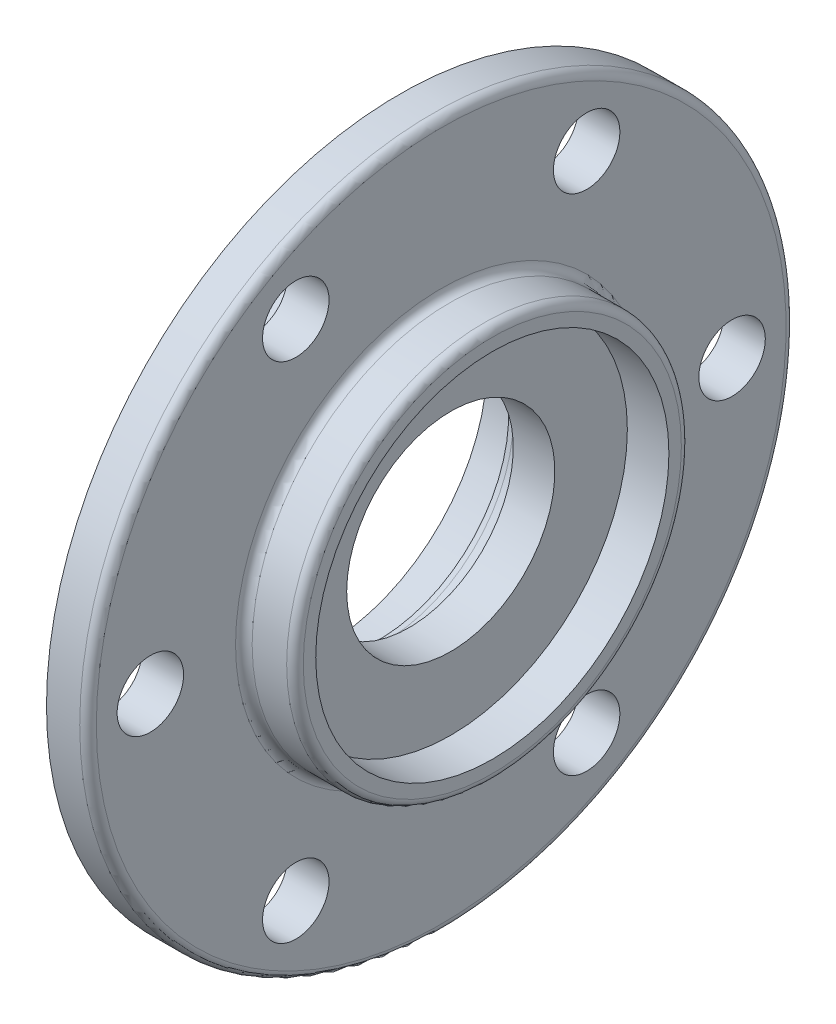
SolidWorks part; units mm, degrees
ref_plane "Front Plane" through (0, 0, 0) normal (0, 0, 1) x (1, 0, 0)
ref_plane "Top Plane" through (0, 0, 0) normal (0, 1, 0) x (1, 0, 0)
ref_plane "Right Plane" through (0, 0, 0) normal (1, 0, 0) x (0, 0, -1)
sketch "Sketch1" plane through (0, 0, 0) normal (0, 0, 1) x (1, 0, 0)
  line L0 (0, 0) -> (85.1756, 0) construction
  line L1 (0, 45) -> (18, 45)
  line L2 (18, 45) -> (18, 85)
  line L3 (18, 85) -> (26, 85)
  line L4 (28, 83) -> (28, 49.5)
  line L5 (30, 47.5) -> (38.3, 47.5)
  line L6 (40.3, 45.5) -> (40.3, 42.5)
  line L7 (40.3, 42.5) -> (30.3, 42.5)
  line L8 (30.3, 42.5) -> (30.3, 25.05)
  line L9 (30.3, 25.05) -> (20.3, 25.05)
  line L10 (20.3, 25.05) -> (20.3, 31)
  line L12 (13, 31.238) -> (13, 37)
  line L13 (11, 39) -> (0, 39)
  line L14 (0, 39) -> (0, 45)
  line L15 (20.3, 31) -> (14.35, 31)
  line L16 (14.35, 31) -> (13, 31.238)
  arc A0 (38.3, 47.5) -> (40.3, 45.5) centre (38.3, 45.5) cw
  arc A1 (13, 37) -> (11, 39) centre (11, 37) ccw
  arc A2 (28, 49.5) -> (30, 47.5) centre (30, 49.5) ccw
  arc A3 (26, 85) -> (28, 83) centre (26, 83) cw
  point P18 (35.3, 42.5)
  point P24 (13, 39)
  dimension "D16" = 2
  dimension "D1" = 50.1
  dimension "D2" = 7.3
  dimension "D3" = 5.95
  dimension "D4" = 10
  dimension "D5" = 62
  dimension "D6" = 90
  dimension "D7" = 78
  dimension "D8" = 170
  dimension "D9" = 13
  dimension "D10" = 10
  dimension "D11" = 85
  dimension "D12" = 10
  dimension "D13" = 5
  dimension "D14" = 10
  dimension "D15" = 18
revolve "Revolve1" add sketch "Sketch1" angle 360 about L0
sketch "Sketch2" plane through (28, 0, 0) normal (1, 0, 0) x (0, 0, -1)
  circle A0 centre (0, 0) radius 70 construction
  circle A1 centre (70, 0) radius 8
  circle A2 centre (35, -60.6218) radius 8
  circle A3 centre (-35, -60.6218) radius 8
  circle A4 centre (-70, 0) radius 8
  circle A5 centre (-35, 60.6218) radius 8
  circle A6 centre (35, 60.6218) radius 8
  point P5 (37.4388, 65.4881)
  point P6 (0, 0)
  point P18 (0, 0)
  dimension "D1" = 140
  dimension "D2" = 16
  dimension "D3" = 6
extrude "Cut-Extrude1" cut sketch "Sketch2" against normal through all both and the other way through all
